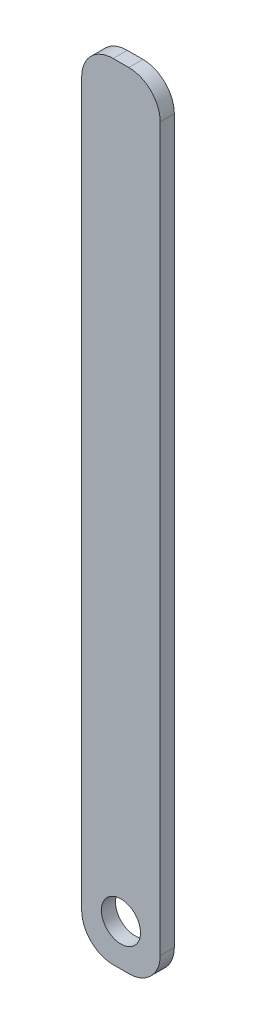
SolidWorks part; units mm, degrees
ref_plane "Front Plane" through (0, 0, 0) normal (0, 0, 1) x (1, 0, 0)
ref_plane "Top Plane" through (0, 0, 0) normal (0, 1, 0) x (1, 0, 0)
ref_plane "Right Plane" through (0, 0, 0) normal (1, 0, 0) x (0, 0, -1)
sketch "Sketch3" plane through (0, 0, 0) normal (0, 0, 1) x (1, 0, 0)
  line L0 (12.7, 0) -> (-12.7, 0)
  line L1 (-12.7, -228.6) -> (-12.7, 228.6)
  line L2 (13.97, 0) -> (-13.97, 0) construction
  line L3 (12.7, -228.6) -> (12.7, 228.6)
  point P4 (0, 0)
  point P9 (-12.7, 0)
  point P11 (12.7, 0)
sketch "Sketch5" plane through (0, 0, 0) normal (0, 0, 1) x (1, 0, 0)
  line L0 (-12.7, 228.6) -> (12.7, 228.6)
  line L1 (-12.7, -228.6) -> (12.7, -228.6)
sketch "Sketch7" plane through (0, 0, 0) normal (0, 0, 1) x (1, 0, 0)
  line L1 (37.3, -271.4) -> (-12.7, -271.4)
  line L2 (37.3, -271.4) -> (37.3, 228.6)
  line L3 (37.3, 228.6) -> (-12.7, 228.6)
  line L4 (-12.7, -271.4) -> (-12.7, 228.6)
  line L5 (37.3, -271.4) -> (-12.7, 228.6) construction
  line L6 (37.3, 228.6) -> (-12.7, -271.4) construction
extrude "Boss-Extrude1" add sketch "Sketch7" along normal mid plane 9
fillet "Fillet1" radius 20 4 edges at (37.3, -271.4, 0) (-12.7, -271.4, 0) (-12.7, 228.6, 0) (37.3, 228.6, 0)
sketch "Sketch8" plane through (0, 0, 4.5) normal (0, 0, 1) x (1, 0, 0)
  line L1 (-12.7, 208.6) -> (37.3, 208.6) construction
  circle A1 centre (12.3, 208.6) radius 5.5
sketch "Sketch9" plane through (0, 0, 4.5) normal (0, 0, 1) x (1, 0, 0)
  line L0 (-12.7, -245.0654) -> (37.3, -245.0654) construction
  line L1 (-12.7, 208.6) -> (-12.7, -251.4) construction
  line L2 (37.3, -251.4) -> (37.3, 208.6) construction
  circle A0 centre (12.3, -245.0654) radius 12.4578
  point P8 (0, 0)
  point P9 (12.3, -54.1086)
  point P10 (12.3, -146.5205)
  point P11 (12.3, -245.0654)
extrude "Cut-Extrude2" cut sketch "Sketch9" against normal blind 10
